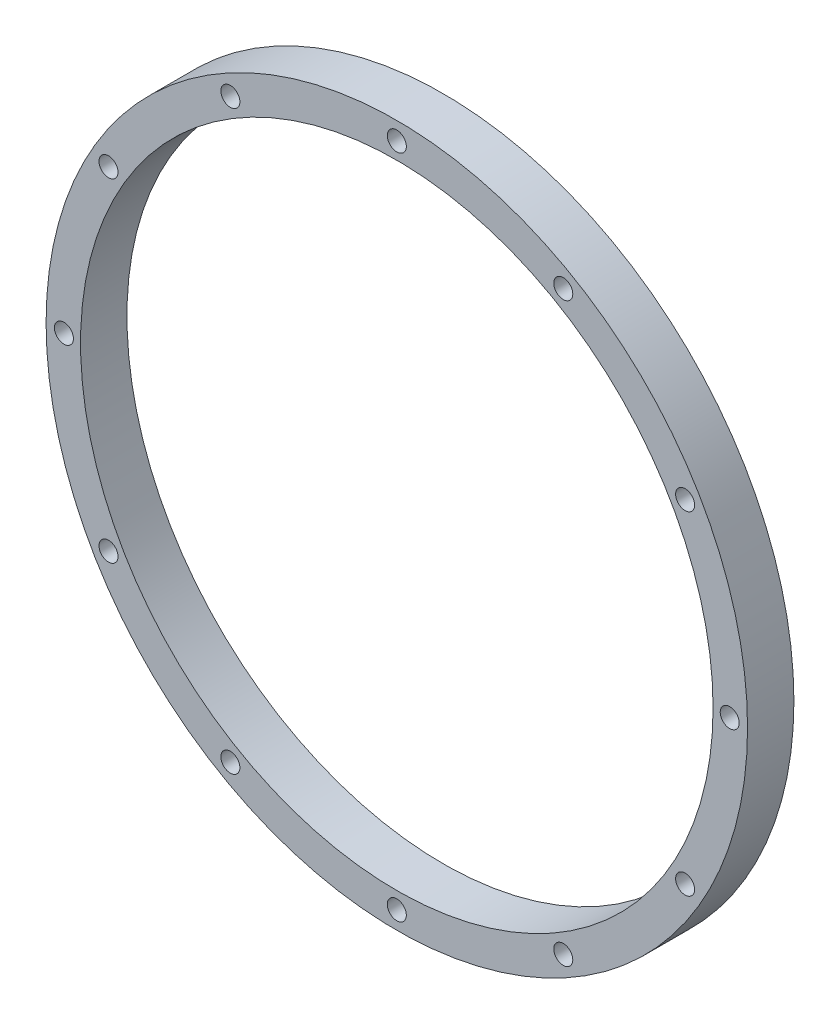
SolidWorks part; units mm, degrees
material "AISI 304"
ref_plane "前视基准面" through (0, 0, 0) normal (0, 0, 1) x (1, 0, 0)
ref_plane "上视基准面" through (0, 0, 0) normal (0, 1, 0) x (1, 0, 0)
ref_plane "右视基准面" through (0, 0, 0) normal (1, 0, 0) x (0, 0, -1)
sketch "草图1" plane through (0, 0, 0) normal (0, 0, 1) x (1, 0, 0)
  circle A0 centre (0, 0) radius 59
  circle A1 centre (0, 0) radius 53.2
  circle A2 centre (0, 0) radius 56 construction
  circle A3 centre (0, 56) radius 1.6
  circle A4 centre (28, 48.4974) radius 1.6
  circle A5 centre (48.4974, 28) radius 1.6
  circle A6 centre (56, 0) radius 1.6
  circle A7 centre (48.4974, -28) radius 1.6
  circle A8 centre (28, -48.4974) radius 1.6
  circle A9 centre (0, -56) radius 1.6
  circle A10 centre (-28, -48.4974) radius 1.6
  circle A11 centre (-48.4974, -28) radius 1.6
  circle A12 centre (-56, 0) radius 1.6
  circle A13 centre (-48.4974, 28) radius 1.6
  circle A14 centre (-28, 48.4974) radius 1.6
  point P31 (0, 0)
  dimension "D1" = 118
  dimension "D2" = 106.4
  dimension "D3" = 3
  dimension "D4" = 3.2
  dimension "D5" = 12
extrude "凸台-拉伸1" add sketch "草图1" along normal blind 7.8
